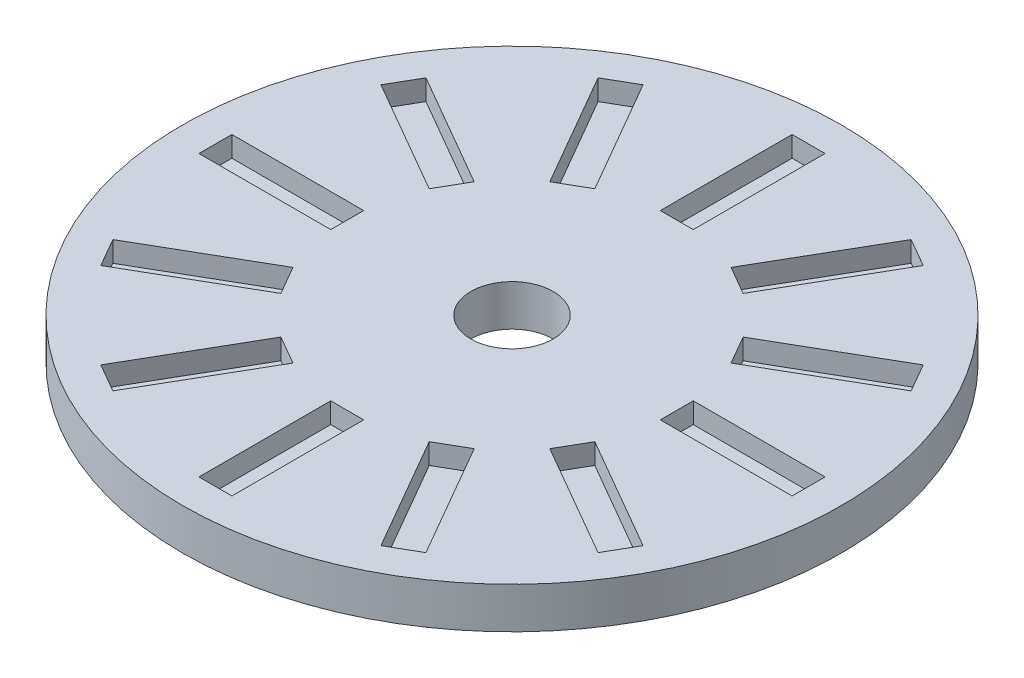
SolidWorks part; units mm, degrees
ref_plane "Front Plane" through (0, 0, 0) normal (0, 0, 1) x (1, 0, 0)
ref_plane "Top Plane" through (0, 0, 0) normal (0, 1, 0) x (1, 0, 0)
ref_plane "Right Plane" through (0, 0, 0) normal (1, 0, 0) x (0, 0, -1)
sketch "Sketch1" plane through (0, 0, 0) normal (0, 1, 0) x (1, 0, 0)
  circle A0 centre (0, 0) radius 101.6
extrude "Boss-Extrude1" add sketch "Sketch1" along normal blind 12.7
sketch "Sketch2" plane through (0, 12.7, 0) normal (0, 1, 0) x (1, 0, 0)
  line L0 (0, 0) -> (0, 50.8) construction
  line L1 (0, 91.44) -> (0, 101.6) construction
  line L2 (0, 50.8) -> (5.08, 50.8)
  line L4 (0, 91.44) -> (5.08, 91.44)
  line L5 (5.08, 50.8) -> (5.08, 91.44)
  line L6 (0, 91.44) -> (-5.08, 91.44)
  line L8 (0, 50.8) -> (-5.08, 50.8)
  line L9 (-5.08, 91.44) -> (-5.08, 50.8)
  line L10 (25.4, 43.9941) -> (29.7994, 41.4541)
  line L11 (29.7994, 41.4541) -> (50.1194, 76.6494)
  line L12 (45.72, 79.1894) -> (50.1194, 76.6494)
  line L13 (45.72, 79.1894) -> (41.3206, 81.7294)
  line L14 (41.3206, 81.7294) -> (21.0006, 46.5341)
  line L15 (25.4, 43.9941) -> (21.0006, 46.5341)
  line L16 (43.9941, 25.4) -> (46.5341, 21.0006)
  line L17 (46.5341, 21.0006) -> (81.7294, 41.3206)
  line L18 (79.1894, 45.72) -> (81.7294, 41.3206)
  line L19 (79.1894, 45.72) -> (76.6494, 50.1194)
  line L20 (76.6494, 50.1194) -> (41.4541, 29.7994)
  line L21 (43.9941, 25.4) -> (41.4541, 29.7994)
  line L22 (50.8, 0) -> (50.8, -5.08)
  line L23 (50.8, -5.08) -> (91.44, -5.08)
  line L24 (91.44, 0) -> (91.44, -5.08)
  line L25 (91.44, 0) -> (91.44, 5.08)
  line L26 (91.44, 5.08) -> (50.8, 5.08)
  line L27 (50.8, 0) -> (50.8, 5.08)
  line L28 (43.9941, -25.4) -> (41.4541, -29.7994)
  line L29 (41.4541, -29.7994) -> (76.6494, -50.1194)
  line L30 (79.1894, -45.72) -> (76.6494, -50.1194)
  line L31 (79.1894, -45.72) -> (81.7294, -41.3206)
  line L32 (81.7294, -41.3206) -> (46.5341, -21.0006)
  line L33 (43.9941, -25.4) -> (46.5341, -21.0006)
  line L34 (25.4, -43.9941) -> (21.0006, -46.5341)
  line L35 (21.0006, -46.5341) -> (41.3206, -81.7294)
  line L36 (45.72, -79.1894) -> (41.3206, -81.7294)
  line L37 (45.72, -79.1894) -> (50.1194, -76.6494)
  line L38 (50.1194, -76.6494) -> (29.7994, -41.4541)
  line L39 (25.4, -43.9941) -> (29.7994, -41.4541)
  line L40 (0, -50.8) -> (-5.08, -50.8)
  line L41 (-5.08, -50.8) -> (-5.08, -91.44)
  line L42 (0, -91.44) -> (-5.08, -91.44)
  line L43 (0, -91.44) -> (5.08, -91.44)
  line L44 (5.08, -91.44) -> (5.08, -50.8)
  line L45 (0, -50.8) -> (5.08, -50.8)
  line L46 (-25.4, -43.9941) -> (-29.7994, -41.4541)
  line L47 (-29.7994, -41.4541) -> (-50.1194, -76.6494)
  line L48 (-45.72, -79.1894) -> (-50.1194, -76.6494)
  line L49 (-45.72, -79.1894) -> (-41.3206, -81.7294)
  line L50 (-41.3206, -81.7294) -> (-21.0006, -46.5341)
  line L51 (-25.4, -43.9941) -> (-21.0006, -46.5341)
  line L52 (-43.9941, -25.4) -> (-46.5341, -21.0006)
  line L53 (-46.5341, -21.0006) -> (-81.7294, -41.3206)
  line L54 (-79.1894, -45.72) -> (-81.7294, -41.3206)
  line L55 (-79.1894, -45.72) -> (-76.6494, -50.1194)
  line L56 (-76.6494, -50.1194) -> (-41.4541, -29.7994)
  line L57 (-43.9941, -25.4) -> (-41.4541, -29.7994)
  line L58 (-50.8, 0) -> (-50.8, 5.08)
  line L59 (-50.8, 5.08) -> (-91.44, 5.08)
  line L60 (-91.44, 0) -> (-91.44, 5.08)
  line L61 (-91.44, 0) -> (-91.44, -5.08)
  line L62 (-91.44, -5.08) -> (-50.8, -5.08)
  line L63 (-50.8, 0) -> (-50.8, -5.08)
  line L64 (-43.9941, 25.4) -> (-41.4541, 29.7994)
  line L65 (-41.4541, 29.7994) -> (-76.6494, 50.1194)
  line L66 (-79.1894, 45.72) -> (-76.6494, 50.1194)
  line L67 (-79.1894, 45.72) -> (-81.7294, 41.3206)
  line L68 (-81.7294, 41.3206) -> (-46.5341, 21.0006)
  line L69 (-43.9941, 25.4) -> (-46.5341, 21.0006)
  line L70 (-25.4, 43.9941) -> (-21.0006, 46.5341)
  line L71 (-21.0006, 46.5341) -> (-41.3206, 81.7294)
  line L72 (-45.72, 79.1894) -> (-41.3206, 81.7294)
  line L73 (-45.72, 79.1894) -> (-50.1194, 76.6494)
  line L74 (-50.1194, 76.6494) -> (-29.7994, 41.4541)
  line L75 (-25.4, 43.9941) -> (-29.7994, 41.4541)
  circle A0 centre (0, 0) radius 50.8 construction
  circle A1 centre (0, 0) radius 91.44 construction
  point P81 (0, 0)
  dimension "D1" = 5.08
  dimension "D2" = 5.08
  dimension "D3" = 12
  dimension "D4" = 40.64
extrude "Cut-Extrude1" cut sketch "Sketch2" against normal blind 6.35
sketch "Sketch3" plane through (0, 12.7, 0) normal (0, 1, 0) x (1, 0, 0)
  circle A0 centre (0, 0) radius 12.7
extrude "Cut-Extrude2" cut sketch "Sketch3" against normal through all both and the other way through all
